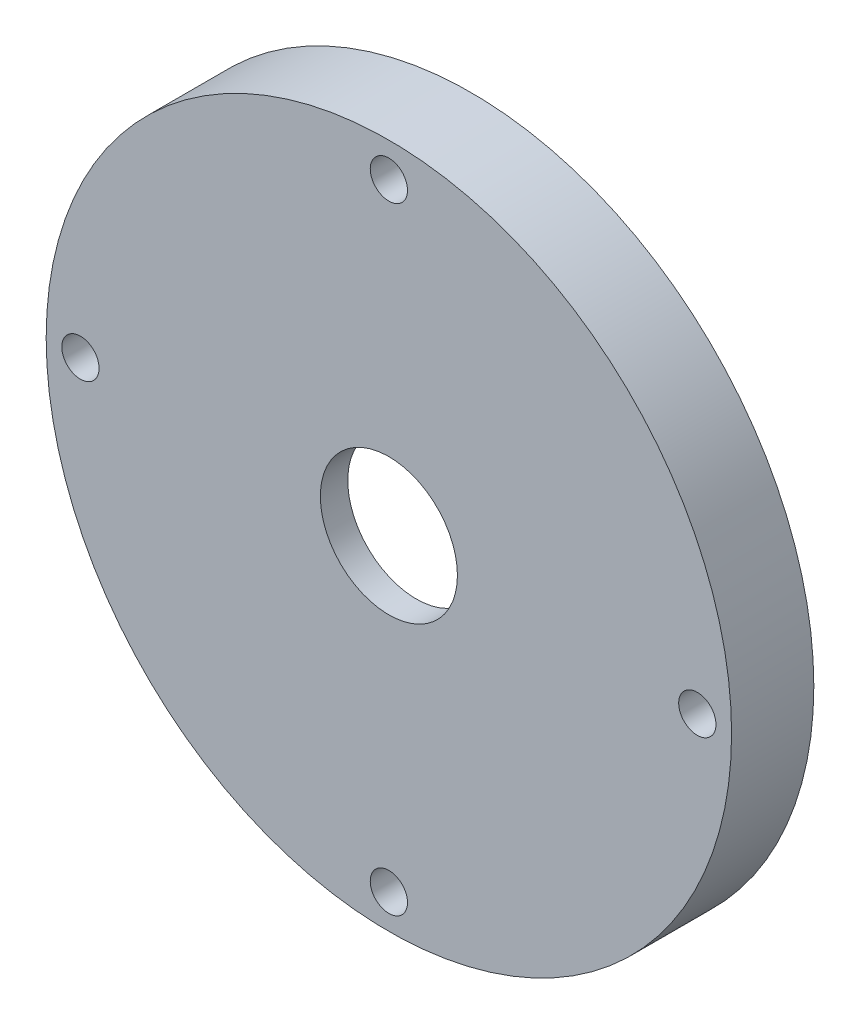
SolidWorks part; units mm, degrees
ref_plane "Front" through (0, 0, 0) normal (0, 0, 1) x (1, 0, 0)
ref_plane "Top" through (0, 0, 0) normal (0, 1, 0) x (1, 0, 0)
ref_plane "Right" through (0, 0, 0) normal (1, 0, 0) x (0, 0, -1)
sketch "Sketch1" plane through (0, 0, 0) normal (0, 0, 1) x (1, 0, 0)
  circle A0 centre (0, 0) radius 31.75
  circle A1 centre (0, 0) radius 21.59
  dimension "D1" = 63.5
  dimension "D2" = 43.18
extrude "Boss-Extrude1" add sketch "Sketch1" along normal blind 5.08
sketch "Sketch2" plane through (0, 0, 5.08) normal (0, 0, 1) x (1, 0, 0)
  circle A0 centre (0, 0) radius 31.75
extrude "Boss-Extrude2" add sketch "Sketch2" along normal blind 2.54
sketch "Sketch3" plane through (0, 0, 0) normal (0, 0, -1) x (-1, 0, 0)
  circle A0 centre (0, 0) radius 28.575 construction
  circle A1 centre (0, 28.575) radius 1.7272
  circle A2 centre (0, 0) radius 28.575 construction
  circle A3 centre (28.575, 0) radius 1.7272
  circle A4 centre (0, 0) radius 28.575 construction
  circle A5 centre (0, -28.575) radius 1.7272
  circle A6 centre (0, 0) radius 28.575 construction
  circle A7 centre (-28.575, 0) radius 1.7272
  circle A8 centre (0, 0) radius 25.019 construction
  point P17 (0, 0)
  dimension "D1" = 57.15
  dimension "D2" = 3.4544
  dimension "D4" = 50.038
  dimension "D3" = 4
extrude "Cut-Extrude1" cut sketch "Sketch3" against normal up to surface (7.62 mm away) up to face at (31.75, 0, 7.62)
sketch "Sketch4" plane through (0, 0, 7.62) normal (0, 0, 1) x (1, 0, 0)
  circle A0 centre (0, 0) radius 6.35
  dimension "D1" = 12.7
extrude "Cut-Extrude2" cut sketch "Sketch4" against normal up to surface (2.54 mm away) up to face at (21.59, 0, 5.08)
